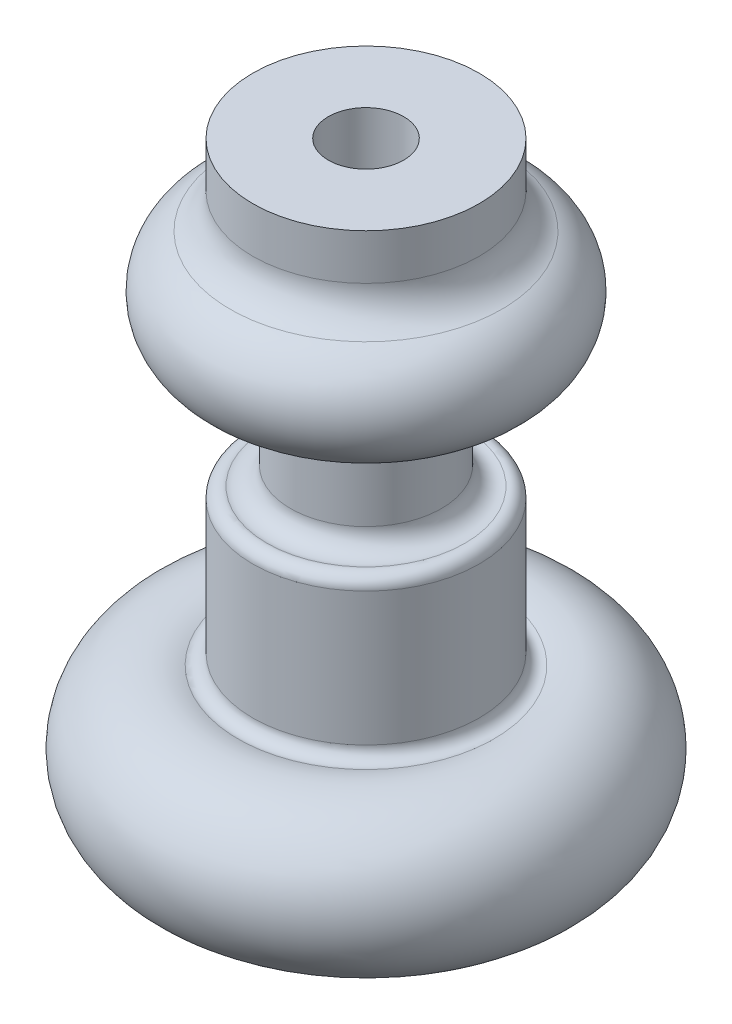
SolidWorks part; units mm, degrees
ref_plane "Front Plane" through (0, 0, 0) normal (0, 0, 1) x (1, 0, 0)
ref_plane "Top Plane" through (0, 0, 0) normal (0, 1, 0) x (1, 0, 0)
ref_plane "Right Plane" through (0, 0, 0) normal (1, 0, 0) x (0, 0, -1)
sketch "Sketch1" plane through (0, 0, 0) normal (0, 0, 1) x (1, 0, 0)
  line L0 (0, 0) -> (0, 75446.3231) construction
  line L1 (0, 0) -> (75446.3231, 0) construction
  line L3 (0, 0) -> (40, 0)
  line L5 (30, 41.9089) -> (30, 77.254)
  line L7 (20, 85) -> (20, 100)
  line L8 (30, 147.9129) -> (30, 160)
  line L9 (30, 160) -> (10, 160)
  line L10 (10, 160) -> (10, 120)
  line L11 (10, 120) -> (0, 120)
  line L12 (0, 120) -> (0, 0)
  arc A0 (40, 0) -> (33.913, 39.0512) centre (40, 20) ccw
  arc A1 (33.913, 39.0512) -> (30, 41.9089) centre (33, 41.9089) cw
  arc A2 (30, 77.254) -> (26.25, 80.1588) centre (27, 77.254) ccw
  arc A3 (26.25, 80.1588) -> (20, 85) centre (25, 85) cw
  arc A4 (20, 100) -> (30, 110) centre (30, 100) cw
  arc A5 (30, 110) -> (36, 138.7477) centre (30, 125) ccw
  arc A6 (36, 138.7477) -> (30, 147.9129) centre (40, 147.9129) cw
  point P5 (25.9722, 78.9124)
  point P11 (34.2165, 39.1679)
  point P17 (0, 0)
  point P30 (0, 0)
  point P31 (34.2165, 39.1474)
  point P32 (0, 0)
  dimension "D1" = 80
  dimension "D4" = 15
  dimension "D10" = 20
  dimension "D11" = 3
  dimension "D12" = 3
  dimension "D13" = 5
  dimension "D14" = 10
  dimension "D15" = 10
  dimension "D2" = 60
  dimension "D3" = 20
  dimension "D5" = 160
  dimension "D6" = 125
  dimension "D7" = 100
  dimension "D8" = 85
  dimension "D9" = 40
  dimension "D16" = 60
  dimension "D17" = 40
revolve "Revolve1" add sketch "Sketch1" angle 360 about L0
